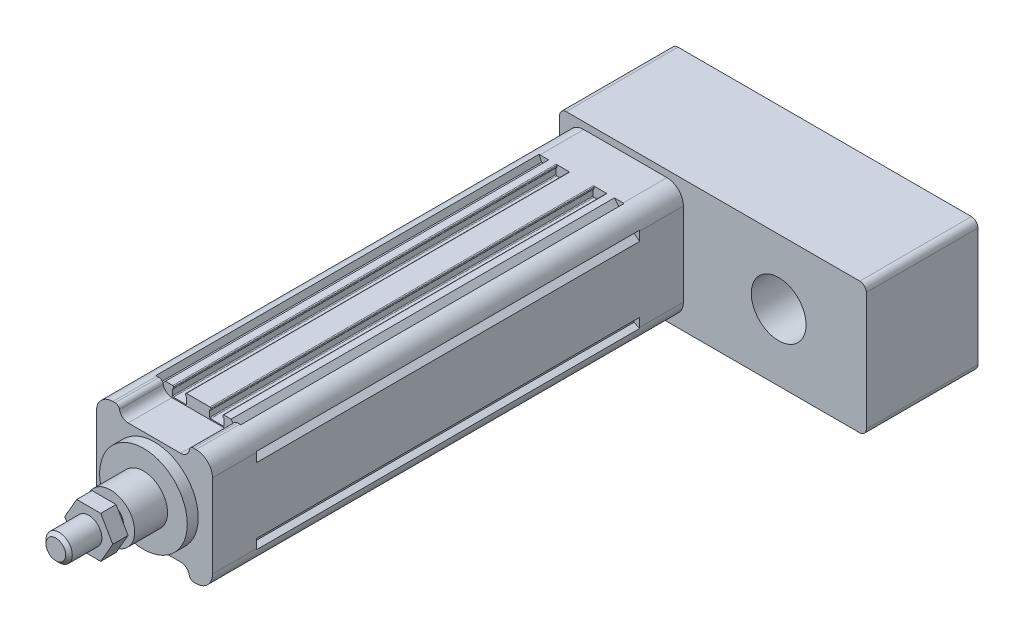
SolidWorks part; units mm, degrees
ref_plane "Front" through (0, 0, 0) normal (0, 0, 1) x (1, 0, 0)
ref_plane "Top" through (0, 0, 0) normal (0, 1, 0) x (1, 0, 0)
ref_plane "Right" through (0, 0, 0) normal (1, 0, 0) x (0, 0, -1)
sketch "草图1" plane through (0, 0, 0) normal (0, 0, 1) x (1, 0, 0)
  line L0 (19.7737, 3) -> (23.3, 3)
  line L1 (23.3, 3) -> (23.3, -3)
  line L2 (23.3, -3) -> (19.7737, -3)
  line L3 (-19.7737, -3) -> (-23.3, -3)
  line L4 (-23.3, -3) -> (-23.3, 3)
  line L5 (-23.3, 3) -> (-19.7737, 3)
  line L6 (-18.2, 24) -> (-19.4434, 26.4869)
  line L7 (-26.4869, 19.4434) -> (-24, 18.2)
  line L8 (-24, 18.2) -> (-24, 17.1)
  line L9 (-24, 17.1) -> (-26.5, 15)
  line L10 (-26.5, 15) -> (-26.5, -15)
  line L11 (-26.5, -15) -> (-24, -17.1)
  line L12 (-24, -17.1) -> (-24, -18.2)
  line L13 (-24, -18.2) -> (-26.4869, -19.4434)
  line L14 (-19.4434, -26.4869) -> (-18.2, -24)
  line L15 (-18.2, -24) -> (-17.1, -24)
  line L16 (-17.1, -24) -> (-15, -26.5)
  line L17 (-15, -26.5) -> (-11.65, -26.5)
  line L18 (-11.25, -26.1) -> (-11.25, -25.6)
  line L19 (-11.65, -25.2) -> (-11.75, -25.2)
  line L20 (-11.75, -25.2) -> (-11.75, -22.4)
  line L21 (-11.35, -22) -> (-5.65, -22)
  line L22 (-5.25, -22.4) -> (-5.25, -25.2)
  line L23 (-5.25, -25.2) -> (-5.35, -25.2)
  line L24 (-5.75, -25.6) -> (-5.75, -26.1)
  line L25 (-5.35, -26.5) -> (5.35, -26.5)
  line L26 (5.75, -26.1) -> (5.75, -25.6)
  line L27 (5.35, -25.2) -> (5.25, -25.2)
  line L28 (5.25, -25.2) -> (5.25, -22.4)
  line L29 (5.65, -22) -> (11.35, -22)
  line L30 (11.75, -22.4) -> (11.75, -25.2)
  line L31 (11.75, -25.2) -> (11.65, -25.2)
  line L32 (11.25, -25.6) -> (11.25, -26.1)
  line L33 (11.65, -26.5) -> (15, -26.5)
  line L34 (15, -26.5) -> (17.1, -24)
  line L35 (17.1, -24) -> (18.2, -24)
  line L36 (18.2, -24) -> (19.4434, -26.4869)
  line L37 (26.4869, -19.4434) -> (24, -18.2)
  line L38 (24, -18.2) -> (24, -17.1)
  line L39 (24, -17.1) -> (26.5, -15)
  line L40 (26.5, -15) -> (26.5, 15)
  line L41 (26.5, 15) -> (24, 17.1)
  line L42 (24, 17.1) -> (24, 18.2)
  line L43 (24, 18.2) -> (26.4869, 19.4434)
  line L44 (19.4434, 26.4869) -> (18.2, 24)
  line L45 (18.2, 24) -> (17.1, 24)
  line L46 (17.1, 24) -> (15, 26.5)
  line L47 (15, 26.5) -> (11.65, 26.5)
  line L48 (11.25, 26.1) -> (11.25, 25.6)
  line L49 (11.65, 25.2) -> (11.75, 25.2)
  line L50 (11.75, 25.2) -> (11.75, 22.4)
  line L51 (11.35, 22) -> (5.65, 22)
  line L52 (5.25, 22.4) -> (5.25, 25.2)
  line L53 (5.25, 25.2) -> (5.35, 25.2)
  line L54 (5.75, 25.6) -> (5.75, 26.1)
  line L55 (5.35, 26.5) -> (-5.35, 26.5)
  line L56 (-5.75, 26.1) -> (-5.75, 25.6)
  line L57 (-5.35, 25.2) -> (-5.25, 25.2)
  line L58 (-5.25, 25.2) -> (-5.25, 22.4)
  line L59 (-5.65, 22) -> (-11.35, 22)
  line L60 (-11.75, 22.4) -> (-11.75, 25.2)
  line L61 (-11.75, 25.2) -> (-11.65, 25.2)
  line L62 (-11.25, 25.6) -> (-11.25, 26.1)
  line L63 (-11.65, 26.5) -> (-15, 26.5)
  line L64 (-15, 26.5) -> (-17.1, 24)
  line L65 (-17.1, 24) -> (-18.2, 24)
  arc A0 (19.7737, 3) -> (-19.7737, 3) centre (0, 0) ccw
  arc A1 (-19.7737, -3) -> (19.7737, -3) centre (0, 0) ccw
  circle A2 centre (19, 19) radius 2.1
  circle A3 centre (19, -19) radius 2.1
  circle A4 centre (-19, -19) radius 2.1
  circle A5 centre (-19, 19) radius 2.1
  arc A6 (-19.4434, 26.4869) -> (-26.4869, 19.4434) centre (-19, 19) ccw
  arc A7 (-26.4869, -19.4434) -> (-19.4434, -26.4869) centre (-19, -19) ccw
  arc A8 (-11.65, -26.5) -> (-11.25, -26.1) centre (-11.65, -26.1) ccw
  arc A9 (-11.25, -25.6) -> (-11.65, -25.2) centre (-11.65, -25.6) ccw
  arc A10 (-11.35, -22) -> (-11.75, -22.4) centre (-11.35, -22.4) ccw
  arc A11 (-5.25, -22.4) -> (-5.65, -22) centre (-5.65, -22.4) ccw
  arc A12 (-5.35, -25.2) -> (-5.75, -25.6) centre (-5.35, -25.6) ccw
  arc A13 (-5.75, -26.1) -> (-5.35, -26.5) centre (-5.35, -26.1) ccw
  arc A14 (5.35, -26.5) -> (5.75, -26.1) centre (5.35, -26.1) ccw
  arc A15 (5.75, -25.6) -> (5.35, -25.2) centre (5.35, -25.6) ccw
  arc A16 (5.65, -22) -> (5.25, -22.4) centre (5.65, -22.4) ccw
  arc A17 (11.75, -22.4) -> (11.35, -22) centre (11.35, -22.4) ccw
  arc A18 (11.65, -25.2) -> (11.25, -25.6) centre (11.65, -25.6) ccw
  arc A19 (11.25, -26.1) -> (11.65, -26.5) centre (11.65, -26.1) ccw
  arc A20 (19.4434, -26.4869) -> (26.4869, -19.4434) centre (19, -19) ccw
  arc A21 (26.4869, 19.4434) -> (19.4434, 26.4869) centre (19, 19) ccw
  arc A22 (11.65, 26.5) -> (11.25, 26.1) centre (11.65, 26.1) ccw
  arc A23 (11.25, 25.6) -> (11.65, 25.2) centre (11.65, 25.6) ccw
  arc A24 (11.35, 22) -> (11.75, 22.4) centre (11.35, 22.4) ccw
  arc A25 (5.25, 22.4) -> (5.65, 22) centre (5.65, 22.4) ccw
  arc A26 (5.35, 25.2) -> (5.75, 25.6) centre (5.35, 25.6) ccw
  arc A27 (5.75, 26.1) -> (5.35, 26.5) centre (5.35, 26.1) ccw
  arc A28 (-5.35, 26.5) -> (-5.75, 26.1) centre (-5.35, 26.1) ccw
  arc A29 (-5.75, 25.6) -> (-5.35, 25.2) centre (-5.35, 25.6) ccw
  arc A30 (-5.65, 22) -> (-5.25, 22.4) centre (-5.65, 22.4) ccw
  arc A31 (-11.75, 22.4) -> (-11.35, 22) centre (-11.35, 22.4) ccw
  arc A32 (-11.65, 25.2) -> (-11.25, 25.6) centre (-11.65, 25.6) ccw
  arc A33 (-11.25, 26.1) -> (-11.65, 26.5) centre (-11.65, 26.1) ccw
extrude "凸台-拉伸1" add sketch "草图1" along normal blind 175
sketch "草图6" plane through (0, 0, 175) normal (0, 0, 1) x (1, 0, 0)
  line L0 (0, 0) -> (19, 0) construction
  line L2 (-26.5, -19) -> (-26.5, 19)
  line L3 (-19, 26.5) -> (-17.9161, 26.5)
  line L4 (26.5, -19) -> (26.5, 19)
  line L5 (-26.5, -26.5) -> (26.5, 26.5) construction
  line L6 (-26.5, 26.5) -> (26.5, -26.5) construction
  line L7 (-12, 21.5) -> (12, 21.5)
  line L9 (19, 26.5) -> (17.9161, 26.5)
  line L10 (19, -26.5) -> (17.9161, -26.5)
  line L11 (-12, -21.5) -> (12, -21.5)
  line L12 (-19, -26.5) -> (-17.9161, -26.5)
  arc A0 (12, 21.5) -> (15.9441, 24.8333) centre (12, 25.5) ccw
  arc A1 (-15.9441, 24.8333) -> (-12, 21.5) centre (-12, 25.5) ccw
  arc A2 (-15.9441, 24.8333) -> (-17.9161, 26.5) centre (-17.9161, 24.5) ccw
  arc A3 (15.9441, 24.8333) -> (17.9161, 26.5) centre (17.9161, 24.5) cw
  arc A4 (-26.5, -19) -> (-19, -26.5) centre (-19, -19) ccw
  arc A5 (19, -26.5) -> (26.5, -19) centre (19, -19) ccw
  arc A6 (26.5, 19) -> (19, 26.5) centre (19, 19) ccw
  arc A7 (-26.5, 19) -> (-19, 26.5) centre (-19, 19) cw
  arc A8 (15.9441, -24.8333) -> (17.9161, -26.5) centre (17.9161, -24.5) ccw
  arc A9 (12, -21.5) -> (15.9441, -24.8333) centre (12, -25.5) cw
  arc A10 (-15.9441, -24.8333) -> (-12, -21.5) centre (-12, -25.5) cw
  arc A11 (-15.9441, -24.8333) -> (-17.9161, -26.5) centre (-17.9161, -24.5) cw
  point P0 (0, 0)
  point P9 (0, 21.5)
  point P13 (20, 20.8461)
  point P16 (-12, 20.8461)
  dimension "D5" = 4
  dimension "D6" = 2
  dimension "D7" = 2
  dimension "D9" = 7.5
  dimension "D1" = 53
  dimension "D2" = 53
  dimension "D3" = 26.5
  dimension "D4" = 24
  dimension "D8" = 5
extrude "凸台-拉伸2" add sketch "草图6" along normal blind 20
sketch "草图7" plane through (0, 0, 195) normal (0, 0, 1) x (1, 0, 0)
  circle A0 centre (0, 0) radius 20
  dimension "D1" = 40
extrude "凸台-拉伸3" add sketch "草图7" along normal blind 5
sketch "草图9" plane through (0, 0, 200) normal (0, 0, 1) x (1, 0, 0)
  circle A0 centre (0, 0) radius 11
  dimension "D1" = 22
extrude "凸台-拉伸4" add sketch "草图9" along normal blind 15
sketch "草图10" plane through (0, 0, 215) normal (0, 0, 1) x (1, 0, 0)
  circle A0 centre (0, 0) radius 6
  dimension "D1" = 12
extrude "凸台-拉伸5" add sketch "草图10" along normal blind 25
sketch "草图11" plane through (0, 0, 0) normal (0, 0, -1) x (-1, 0, 0)
  line L1 (-19, -26.5) -> (19, -26.5)
  line L2 (-26.5, -19) -> (-26.5, 19)
  line L3 (-19, 26.5) -> (19, 26.5)
  line L4 (26.5, -19) -> (26.5, 19)
  line L5 (-26.5, -26.5) -> (26.5, 26.5) construction
  line L6 (-26.5, 26.5) -> (26.5, -26.5) construction
  arc A0 (-26.5, -19) -> (-19, -26.5) centre (-19, -19) ccw
  arc A1 (19, -26.5) -> (26.5, -19) centre (19, -19) ccw
  arc A2 (26.5, 19) -> (19, 26.5) centre (19, 19) ccw
  arc A3 (-26.5, 19) -> (-19, 26.5) centre (-19, 19) cw
  point P0 (0, 0)
  dimension "D3" = 7.5
  dimension "D1" = 53
  dimension "D2" = 53
extrude "凸台-拉伸6" add sketch "草图11" along normal blind 20
sketch "草图12" plane through (0, 0, -20) normal (0, 0, -1) x (-1, 0, 0)
  line L1 (-107, -30.4042) -> (27, -30.4042)
  line L2 (-110, -27.4042) -> (-110, 26.5958)
  line L3 (-107, 29.5958) -> (27, 29.5958)
  line L4 (30, -27.4042) -> (30, 26.5958)
  line L5 (-110, -30.4042) -> (30, 29.5958) construction
  line L6 (-110, 29.5958) -> (30, -30.4042) construction
  arc A0 (27, 29.5958) -> (30, 26.5958) centre (27, 26.5958) cw
  arc A1 (30, -27.4042) -> (27, -30.4042) centre (27, -27.4042) cw
  arc A2 (-110, -27.4042) -> (-107, -30.4042) centre (-107, -27.4042) ccw
  arc A3 (-110, 26.5958) -> (-107, 29.5958) centre (-107, 26.5958) cw
  point P0 (-40, -0.4042)
  dimension "D4" = 3
  dimension "D1" = 60
  dimension "D2" = 140
  dimension "D3" = 30
extrude "凸台-拉伸7" add sketch "草图12" along normal blind 51
sketch "草图13" plane through (0, 0, -20) normal (0, 0, 1) x (1, 0, 0)
  circle A0 centre (70, 0) radius 12.5
  dimension "D2" = 25
  dimension "D1" = 70
extrude "切除-拉伸2" cut sketch "草图13" against normal blind 30
hole_wizard "M6 螺纹孔1" positions "草图14" profile "草图15" tap size "M6" standard "GB"
sketch "草图14" plane through (0, 0, -71) normal (0, 0, -1) x (-1, 0, 0)
  line L0 (30, -27.4042) -> (30, 26.5958) construction
  point P0 (19, -19)
  dimension "D1" = 11
  dimension "D2" = 19
sketch "草图15" plane through (-19, -19, -71) normal (1, 0, 0) x (0, 1, 0)
  line L0 (0, 0) -> (0, 16.5022)
  line L1 (0, 16.5022) -> (2.5, 15)
  line L2 (2.5, 15) -> (2.5, 0)
  line L5 (2.5, 0) -> (0, 0)
  line L10 (0, 16.5022) -> (-2.5, 15) construction
  line L11 (0, -6.35) -> (0, 107.95) construction
  dimension "螺纹孔钻头直径" = 5
  dimension "螺纹孔钻头深度" = 15
  dimension "导头角度" = 118
cosmetic thread "孔螺蚊线4" parameters "D1"=12, "D2"=6
pattern_linear "阵列(线性)1" count 2 spacing 38 along (0, 1, 0) count 2 spacing 38 along (1, 0, 0) of "M6 螺纹孔1"
hole_wizard "M6 螺纹孔2" positions "草图16" profile "草图17" tap size "M6" standard "GB"
sketch "草图16" plane through (0, 0, -71) normal (0, 0, -1) x (-1, 0, 0)
  circle A1 centre (-19, 19) radius 2.5 construction
  circle A2 centre (-19, -19) radius 2.5 construction
  point P0 (-84, -19)
  point P2 (-84, 19)
  dimension "D3" = 65
  dimension "D1" = 19
  dimension "D2" = 19
  dimension "D4" = 65
sketch "草图17" plane through (84, -19, -71) normal (1, 0, 0) x (0, 1, 0)
  line L0 (0, 0) -> (0, 16.5022)
  line L1 (0, 16.5022) -> (2.5, 15)
  line L2 (2.5, 15) -> (2.5, 0)
  line L5 (2.5, 0) -> (0, 0)
  line L10 (0, 16.5022) -> (-2.5, 15) construction
  line L11 (0, -6.35) -> (0, 107.95) construction
  dimension "螺纹孔钻头直径" = 5
  dimension "螺纹孔钻头深度" = 15
  dimension "导头角度" = 118
cosmetic thread "孔螺蚊线5" parameters "D1"=12, "D2"=6
cosmetic thread "孔螺蚊线6" parameters "D1"=12, "D2"=6
hole_wizard "M6 螺纹孔3" positions "草图19" profile "草图20" tap size "M6" standard "GB"
sketch "草图19" plane through (-26.5, 0, 0) normal (-1, 0, 0) x (0, 0, 1)
  line L0 (195, 19) -> (195, -19) construction
  point P0 (185, 11)
  point P2 (185, -11)
  dimension "D1" = 10
  dimension "D2" = 10
  dimension "D3" = 22
  dimension "D4" = 11
sketch "草图20" plane through (-26.5, 11, 185) normal (0, 1, 0) x (0, 0, 1)
  line L0 (0, 0) -> (0, 16.5022)
  line L1 (0, 16.5022) -> (2.5, 15)
  line L2 (2.5, 15) -> (2.5, 0)
  line L5 (2.5, 0) -> (0, 0)
  line L10 (0, 16.5022) -> (-2.5, 15) construction
  line L11 (0, -6.35) -> (0, 107.95) construction
  dimension "螺纹孔钻头直径" = 5
  dimension "螺纹孔钻头深度" = 15
  dimension "导头角度" = 118
cosmetic thread "孔螺蚊线7" parameters "D1"=12, "D2"=6
cosmetic thread "孔螺蚊线8" parameters "D1"=12, "D2"=6
hole_wizard "M6 螺纹孔4" positions "草图21" profile "草图22" tap size "M6" standard "GB"
sketch "草图21" plane through (-26.5, 0, 0) normal (-1, 0, 0) x (0, 0, 1)
  line L0 (-20, -27.4042) -> (-20, 26.5958) construction
  line L1 (-20, -19) -> (-20, 19) construction
  point P0 (-10, 11)
  point P2 (-10, -11)
  dimension "D1" = 10
  dimension "D2" = 10
  dimension "D3" = 11
  dimension "D4" = 11
sketch "草图22" plane through (-26.5, 11, -10) normal (0, 1, 0) x (0, 0, 1)
  line L0 (0, 0) -> (0, 16.5022)
  line L1 (0, 16.5022) -> (2.5, 15)
  line L2 (2.5, 15) -> (2.5, 0)
  line L5 (2.5, 0) -> (0, 0)
  line L10 (0, 16.5022) -> (-2.5, 15) construction
  line L11 (0, -6.35) -> (0, 107.95) construction
  dimension "螺纹孔钻头直径" = 5
  dimension "螺纹孔钻头深度" = 15
  dimension "导头角度" = 118
cosmetic thread "孔螺蚊线9" parameters "D1"=12, "D2"=6
cosmetic thread "孔螺蚊线10" parameters "D1"=12, "D2"=6
chamfer "倒角1" distance 1.5 angle 45 1 edges at (6, 0, 240)
sketch "草图23" plane through (0, 0, 215) normal (0, 0, 1) x (1, 0, 0)
  line L1 (10.9697, 0) -> (5.4848, 9.5)
  line L2 (5.4848, 9.5) -> (-5.4848, 9.5)
  line L3 (-5.4848, 9.5) -> (-10.9697, 0)
  line L4 (-10.9697, 0) -> (-5.4848, -9.5)
  line L5 (-5.4848, -9.5) -> (5.4848, -9.5)
  line L6 (5.4848, -9.5) -> (10.9697, 0)
  circle A0 centre (0, 0) radius 9.5 construction
  dimension "D1" = 19
extrude "凸台-拉伸8" add sketch "草图23" along normal blind 7 from offset 3
